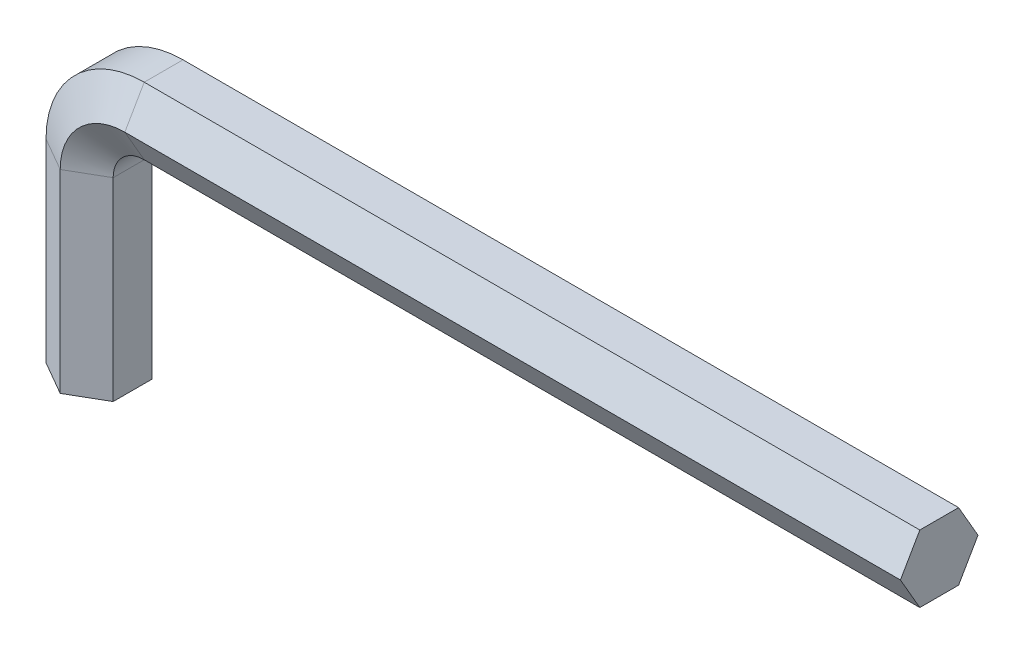
SolidWorks part; units mm, degrees
ref_plane "Front Plane" through (0, 0, 0) normal (0, 0, 1) x (1, 0, 0)
ref_plane "Top Plane" through (0, 0, 0) normal (0, 1, 0) x (1, 0, 0)
ref_plane "Right Plane" through (0, 0, 0) normal (1, 0, 0) x (0, 0, -1)
sketch "Sketch1" plane through (0, 0, 0) normal (0, 0, 1) x (1, 0, 0)
  line L0 (62.3716, 20.2979) -> (-537.6284, 20.2979)
  line L1 (-587.6284, -29.7021) -> (-587.6284, -179.7021)
  arc A0 (-537.6284, 20.2979) -> (-587.6284, -29.7021) centre (-537.6284, -29.7021) ccw
ref_plane "Plane1" through (62.3716, 20.2979, 0) normal (-1, 0, 0) x (0, 0, 1)
sketch "Sketch2" plane through (62.3716, 20.2979, 0) normal (-1, 0, 0) x (0, 0, 1)
  line L0 (0, -50) -> (0, 0) construction
  line L1 (30, 0) -> (15, 25.9808)
  line L2 (15, 25.9808) -> (-15, 25.9808)
  line L3 (-15, 25.9808) -> (-30, 0)
  line L4 (-30, 0) -> (-15, -25.9808)
  line L5 (-15, -25.9808) -> (15, -25.9808)
  line L6 (15, -25.9808) -> (30, 0)
  circle A0 centre (0, 0) radius 25.9808 construction
sweep "Sweep1" add profiles "Sketch2" path "Sketch1"
